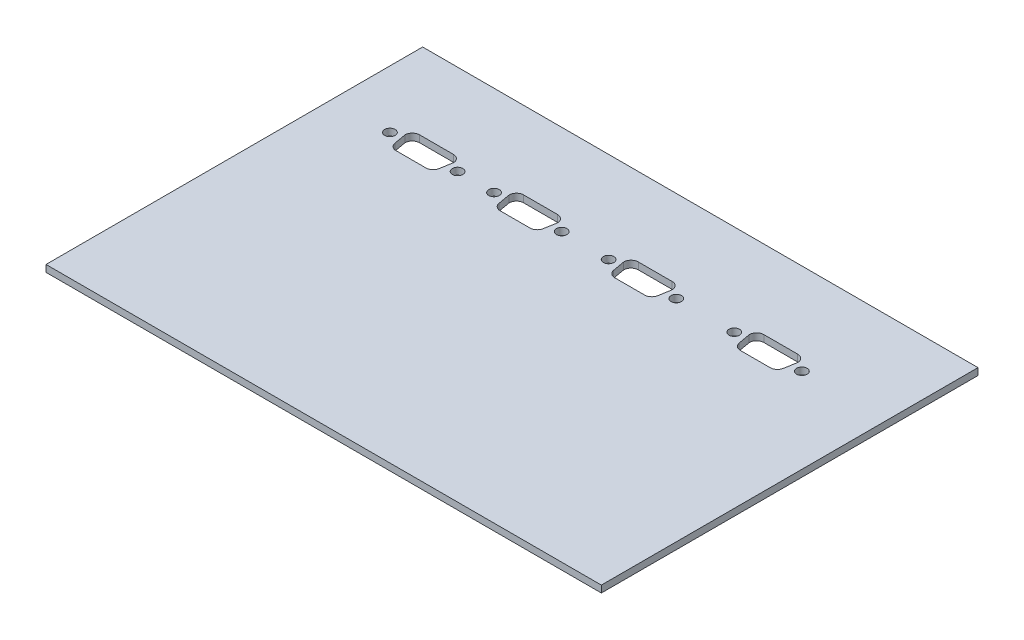
SolidWorks part; units mm, degrees
ref_plane "Front Plane" through (0, 0, 0) normal (0, 0, 1) x (1, 0, 0)
ref_plane "Top Plane" through (0, 0, 0) normal (0, 1, 0) x (1, 0, 0)
ref_plane "Right Plane" through (0, 0, 0) normal (1, 0, 0) x (0, 0, -1)
sketch "Sketch1" plane through (0, 0, 0) normal (0, 1, 0) x (1, 0, 0)
  line L1 (-102.5808, -69.5721) -> (102.5808, -69.5721)
  line L2 (-102.5808, -69.5721) -> (-102.5808, 69.5721)
  line L3 (-102.5808, 69.5721) -> (102.5808, 69.5721)
  line L4 (102.5808, -69.5721) -> (102.5808, 69.5721)
  line L5 (-102.5808, -69.5721) -> (102.5808, 69.5721) construction
  line L6 (-102.5808, 69.5721) -> (102.5808, -69.5721) construction
  point P0 (0, 0)
extrude "Boss-Extrude1" add sketch "Sketch1" along normal blind 2.54
sketch "Sketch3" plane through (0, 2.54, 0) normal (0, 1, 0) x (1, 0, 0)
  line B0 (-62.5359, 40.9035) -> (-75.0581, 40.9035)
  line B1 (-77.7241, 38.1643) -> (-76.9341, 33.684)
  line B2 (-74.3076, 31.4801) -> (-63.2863, 31.4801)
  line B3 (-60.6598, 33.684) -> (-59.8698, 38.1643)
  arc B4 (-59.8698, 38.1643) -> (-62.5359, 40.9035) centre (-62.5359, 38.2365) ccw
  arc B5 (-75.0581, 40.9035) -> (-77.7241, 38.1643) centre (-75.0581, 38.2365) ccw
  arc B6 (-76.9341, 33.684) -> (-74.3076, 31.4801) centre (-74.3076, 34.1471) ccw
  arc B7 (-63.2863, 31.4801) -> (-60.6598, 33.684) centre (-63.2863, 34.1471) ccw
  circle B8 centre (-81.2938, 36.1918) radius 1.9304
  circle B9 centre (-56.3002, 36.1918) radius 1.9304
  line B10 (-24.0746, 40.9035) -> (-36.5968, 40.9035)
  line B11 (-39.2628, 38.1643) -> (-38.4728, 33.684)
  line B12 (-35.8463, 31.4801) -> (-24.8251, 31.4801)
  line B13 (-22.1986, 33.684) -> (-21.4086, 38.1643)
  arc B14 (-21.4086, 38.1643) -> (-24.0746, 40.9035) centre (-24.0746, 38.2365) ccw
  arc B15 (-36.5968, 40.9035) -> (-39.2628, 38.1643) centre (-36.5968, 38.2365) ccw
  arc B16 (-38.4728, 33.684) -> (-35.8463, 31.4801) centre (-35.8463, 34.1471) ccw
  arc B17 (-24.8251, 31.4801) -> (-22.1986, 33.684) centre (-24.8251, 34.1471) ccw
  circle B18 centre (-42.8325, 36.1918) radius 1.9304
  circle B19 centre (-17.8389, 36.1918) radius 1.9304
  line B20 (18.5287, 40.6358) -> (6.0065, 40.6358)
  line B21 (3.3404, 37.8966) -> (4.1304, 33.4163)
  line B22 (6.7569, 31.2124) -> (17.7782, 31.2124)
  line B23 (20.4047, 33.4163) -> (21.1947, 37.8966)
  arc B24 (21.1947, 37.8966) -> (18.5287, 40.6358) centre (18.5287, 37.9688) ccw
  arc B25 (6.0065, 40.6358) -> (3.3404, 37.8966) centre (6.0065, 37.9688) ccw
  arc B26 (4.1304, 33.4163) -> (6.7569, 31.2124) centre (6.7569, 33.8794) ccw
  arc B27 (17.7782, 31.2124) -> (20.4047, 33.4163) centre (17.7782, 33.8794) ccw
  circle B28 centre (-0.2292, 35.9241) radius 1.9304
  circle B29 centre (24.7644, 35.9241) radius 1.9304
  line B30 (64.9781, 40.5856) -> (52.4559, 40.5856)
  line B31 (49.7898, 37.8464) -> (50.5798, 33.3661)
  line B32 (53.2063, 31.1622) -> (64.2276, 31.1622)
  line B33 (66.8541, 33.3661) -> (67.6441, 37.8464)
  arc B34 (67.6441, 37.8464) -> (64.9781, 40.5856) centre (64.9781, 37.9186) ccw
  arc B35 (52.4559, 40.5856) -> (49.7898, 37.8464) centre (52.4559, 37.9186) ccw
  arc B36 (50.5798, 33.3661) -> (53.2063, 31.1622) centre (53.2063, 33.8292) ccw
  arc B37 (64.2276, 31.1622) -> (66.8541, 33.3661) centre (64.2276, 33.8292) ccw
  circle B38 centre (46.2202, 35.8739) radius 1.9304
  circle B39 centre (71.2138, 35.8739) radius 1.9304
sketch_block_instance "VGA-Cutout-1"
sketch_block "Block1"
sketch_block_instance "Block1-1"
sketch_block_instance "Block1-2"
sketch_block_instance "Block1-3"
extrude "Cut-Extrude1" cut sketch "Sketch3" against normal through all
